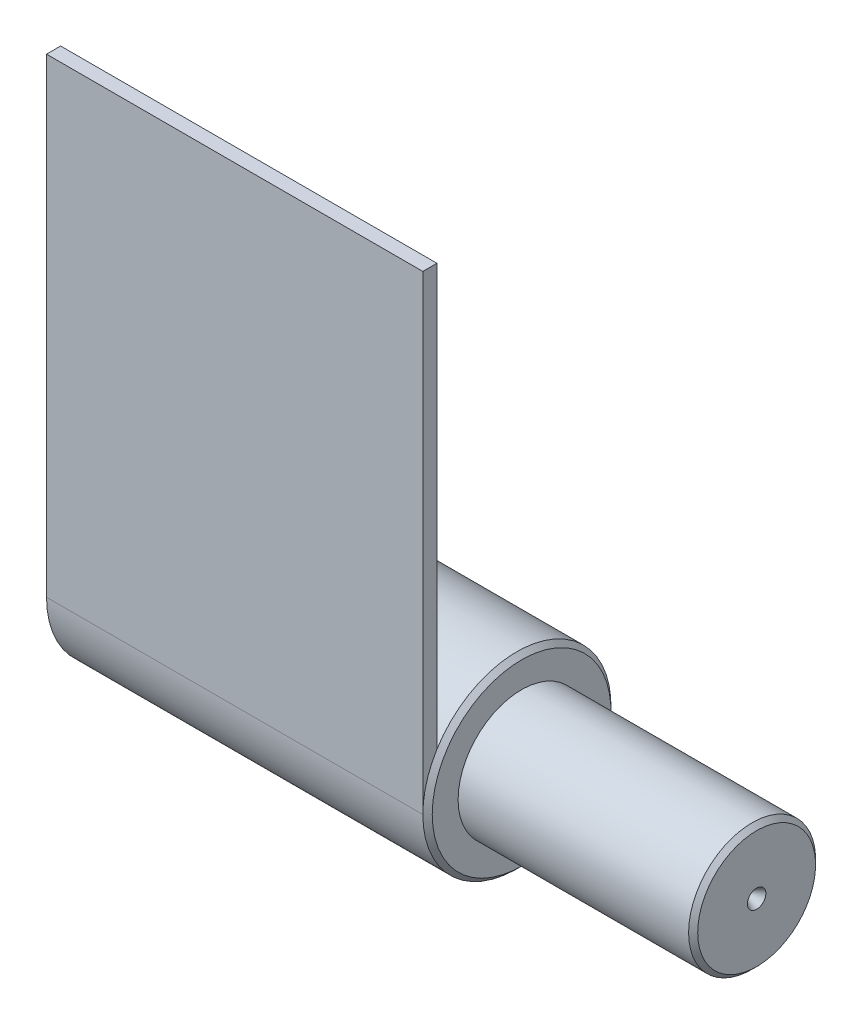
SolidWorks part; units mm, degrees
ref_plane "Спереди" through (0, 0, 0) normal (0, 0, 1) x (1, 0, 0)
ref_plane "Сверху" through (0, 0, 0) normal (0, 1, 0) x (1, 0, 0)
ref_plane "Справа" through (0, 0, 0) normal (1, 0, 0) x (0, 0, -1)
sketch "Эскиз2" plane through (0, 0, 0) normal (0, 1, 0) x (1, 0, 0)
  line L0 (-45.5275, 22.3375) -> (34.4725, 22.3375)
  line L1 (35.4725, 21.3375) -> (35.4725, 15.8375)
  line L2 (35.4725, 15.8375) -> (84.4725, 15.8375)
  line L3 (-47.5275, 20.3375) -> (-47.5275, 2.3375)
  line L4 (85.4416, 14.8685) -> (85.4416, 4.2964)
  line L5 (-47.5275, 2.3375) -> (82.2592, 2.3375)
  line L6 (34.4725, 22.3375) -> (35.4725, 21.3375)
  line L7 (-58.608, 2.3375) -> (159.8552, 2.3375) construction
  line L8 (84.4725, 15.8375) -> (85.4416, 14.8685)
  line L9 (-45.5275, 22.3375) -> (-47.5275, 20.3375)
  line L10 (82.2592, 2.3375) -> (85.4416, 4.2964)
  point P1 (35.4725, 22.3375)
  point P4 (85.4725, 15.8375)
  point P10 (-47.5275, 22.3375)
  dimension "D1" = 20
  dimension "D2" = 13.5
  dimension "D3" = 2
  dimension "D4" = 45
revolve "Повернуть1" add sketch "Эскиз2" angle 360 about L7
sketch "Эскиз3" plane through (0, 0, 0) normal (0, 1, 0) x (1, 0, 0)
  line L0 (34.4725, -17.6625) -> (34.4725, 22.3375) construction
  line L1 (-45.5275, -17.6625) -> (34.4725, -17.6625)
  line L2 (-45.5275, -17.6625) -> (-45.5275, -14.6624)
  line L3 (-45.5275, -14.6624) -> (34.4725, -14.6624)
  line L4 (34.4725, -17.6625) -> (34.4725, -14.6624)
extrude "Бобышка-Вытянуть1" add sketch "Эскиз3" along normal blind 100
